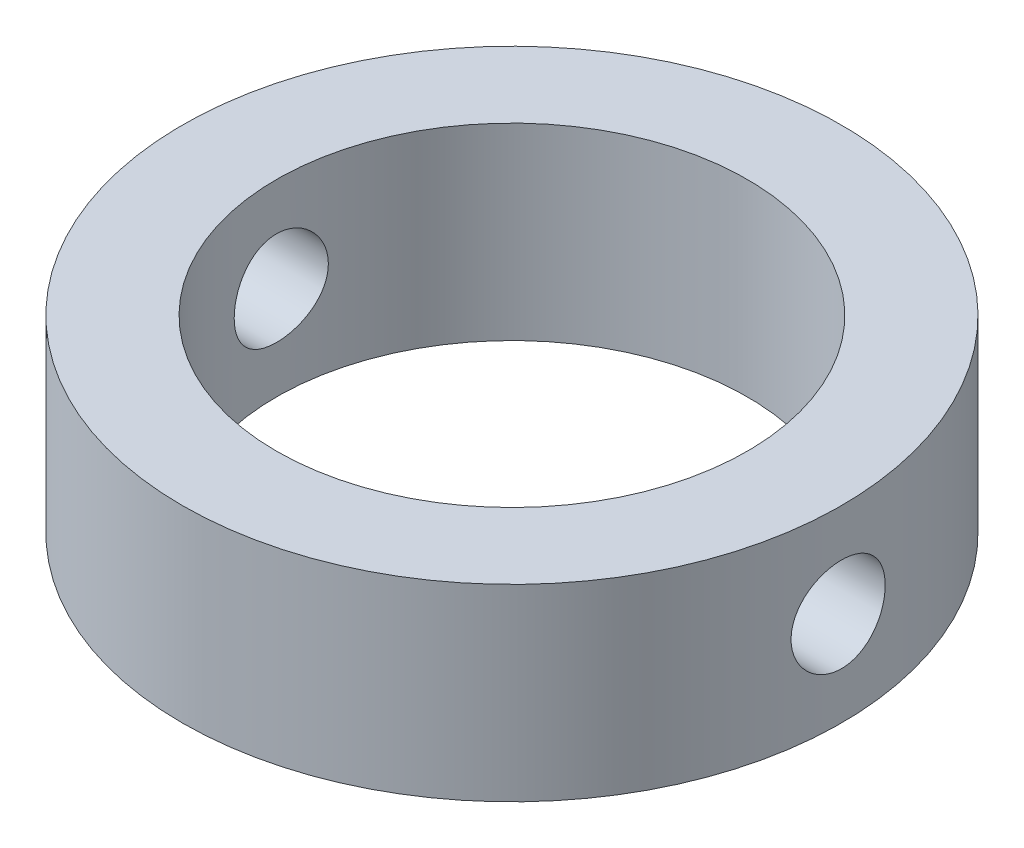
SolidWorks part; units mm, degrees
ref_plane "Front Plane" through (0, 0, 0) normal (0, 0, 1) x (1, 0, 0)
ref_plane "Top Plane" through (0, 0, 0) normal (0, 1, 0) x (1, 0, 0)
ref_plane "Right Plane" through (0, 0, 0) normal (1, 0, 0) x (0, 0, -1)
sketch "Sketch1" plane through (0, 0, 0) normal (0, 1, 0) x (1, 0, 0)
  circle A0 centre (0, 0) radius 35
  circle A1 centre (0, 0) radius 25
  dimension "D1" = 70
  dimension "D2" = 50
extrude "Boss-Extrude1" add sketch "Sketch1" along normal blind 20
ref_plane "Plane1" through (35, 0, 0) normal (1, 0, 0) x (0, 0, -1)
sketch "Sketch2" plane through (35, 0, 0) normal (1, 0, 0) x (0, 0, -1)
  circle A0 centre (0, 10) radius 5
  dimension "D1" = 10
extrude "Cut-Extrude1" cut sketch "Sketch2" against normal through all
